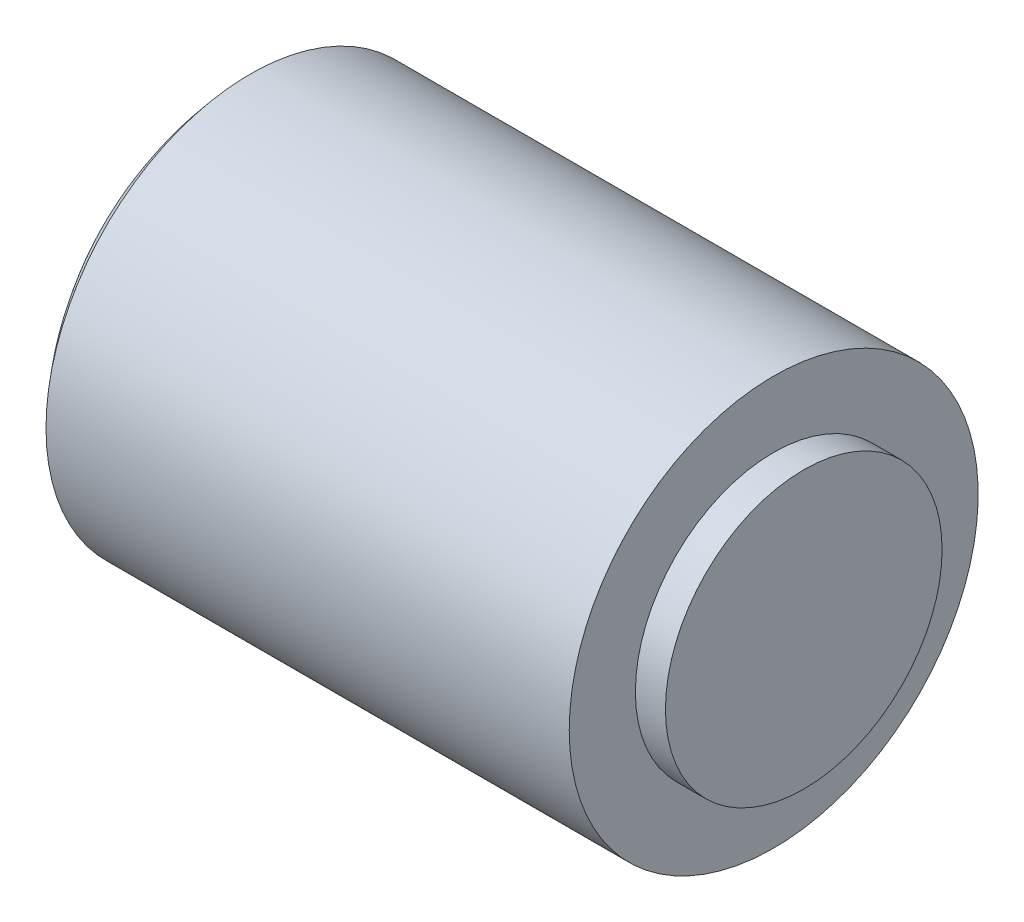
SolidWorks part; units mm, degrees
ref_plane "Front" through (0, 0, 0) normal (0, 0, 1) x (1, 0, 0)
ref_plane "Top" through (0, 0, 0) normal (0, 1, 0) x (1, 0, 0)
ref_plane "Right" through (0, 0, 0) normal (1, 0, 0) x (0, 0, -1)
sketch "Sketch1" plane through (0, 0, 0) normal (0, 1, 0) x (1, 0, 0)
  line L0 (87, 23) -> (92, 23)
  line L1 (0, 0) -> (87, 0)
  line L2 (0, 0) -> (0, 34) construction
  line L3 (0, 34) -> (87, 34)
  line L4 (87, 0) -> (87, 34) construction
  line L5 (92, 23) -> (92, 0)
  line L6 (92, 0) -> (87, 0)
  line L7 (-13, 0) -> (0, 0)
  line L8 (87, 34) -> (87, 23)
  arc A0 (-13, 0) -> (0, 34) centre (37.9615, 0) cw
  point P7 (89.5, 23)
  dimension "D5" = 105
  dimension "D1" = 87
  dimension "D2" = 5
  dimension "D3" = 34
  dimension "D4" = 23
revolve "Revolve1" add sketch "Sketch1" angle 360 about L1
